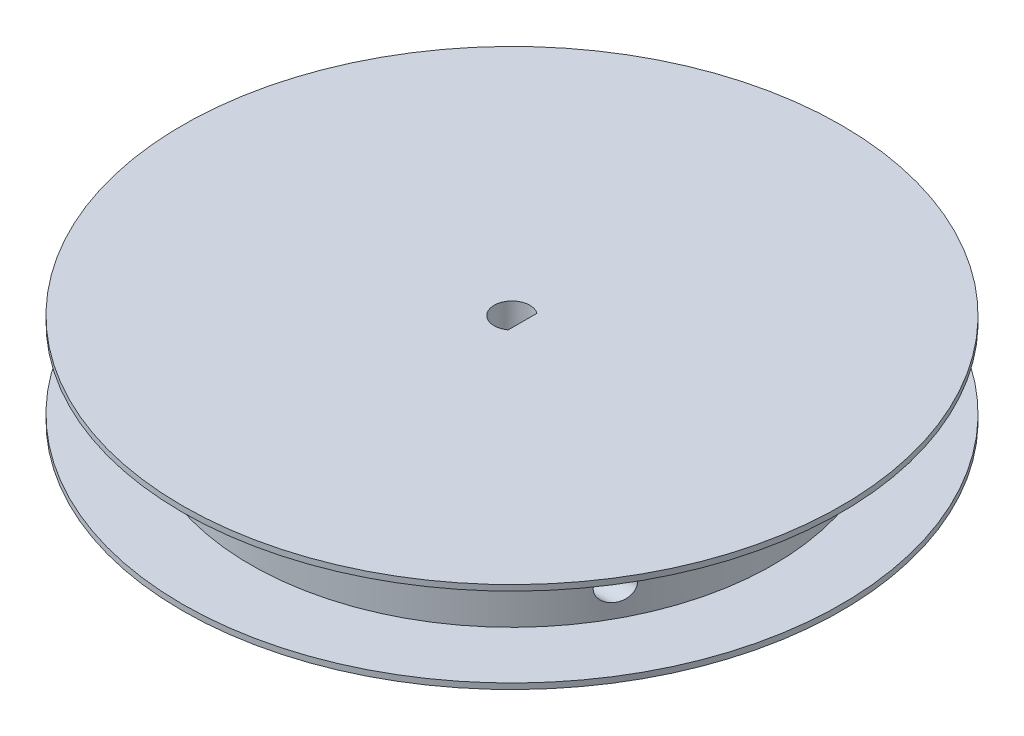
SolidWorks part; units mm, degrees
ref_plane "前基準面" through (0, 0, 0) normal (0, 0, 1) x (1, 0, 0)
ref_plane "上基準面" through (0, 0, 0) normal (0, 1, 0) x (1, 0, 0)
ref_plane "右基準面" through (0, 0, 0) normal (1, 0, 0) x (0, 0, -1)
sketch "草圖1" plane through (0, 0, 0) normal (0, 1, 0) x (1, 0, 0)
  circle A0 centre (0, 0) radius 9
  dimension "D1" = 18
extrude "填料-伸長1" add sketch "草圖1" against normal blind 8
sketch "草圖2" plane through (0, -8, 0) normal (0, -1, 0) x (-1, 0, 0)
  line L1 (-0.93, -1.2649) -> (-0.93, 1.2649)
  circle A0 centre (0, 0) radius 1.57
extrude "除料-伸長1" cut sketch "草圖2" against normal through all contours L1 A0
sketch "草圖3" plane through (0, -8, 0) normal (0, -1, 0) x (-1, 0, 0)
  circle A0 centre (0, 0) radius 14
  circle A1 centre (0, 0) radius 9
sketch "草圖5" plane through (0, 0, 0) normal (0, 1, 0) x (-1, 0, 0)
  circle A0 centre (0, 0) radius 14
  circle A1 centre (0, 0) radius 9
  dimension "D1" = 28
sketch "草圖6" plane through (0, 0, 0) normal (1, 0, 0) x (0, 0, -1)
  circle A0 centre (-8.2974, 2.581) radius 0.4984
sketch "草圖7" plane through (0, -8, 0) normal (0, -1, 0) x (-1, 0, 0)
  circle A0 centre (0, 0) radius 9
  circle A1 centre (0, 0) radius 23
extrude "填料-伸長2" add sketch "草圖7" against normal blind 8
sketch "草圖8" plane through (0, 0, 0) normal (0, 1, 0) x (1, 0, 0)
  circle A0 centre (0, 0) radius 29
  circle A1 centre (0, 0) radius 23
extrude "填料-伸長3" add sketch "草圖8" against normal blind 0.5
sketch "草圖9" plane through (0, -8, 0) normal (0, -1, 0) x (1, 0, 0)
  circle A0 centre (0, 0) radius 23
  circle A1 centre (0, 0) radius 29
extrude "填料-伸長4" add sketch "草圖9" against normal blind 0.5
sketch "草圖10" plane through (0, 0, 0) normal (1, 0, 0) x (0, 0, -1)
  circle A0 centre (-11.0333, -4.9876) radius 1.2598
extrude "除料-伸長2" cut sketch "草圖10" against normal mid plane 50
sketch "草圖11" plane through (0, -7.5, 0) normal (0, 1, 0) x (1, 0, 0)
  circle A0 centre (0, 0) radius 23
